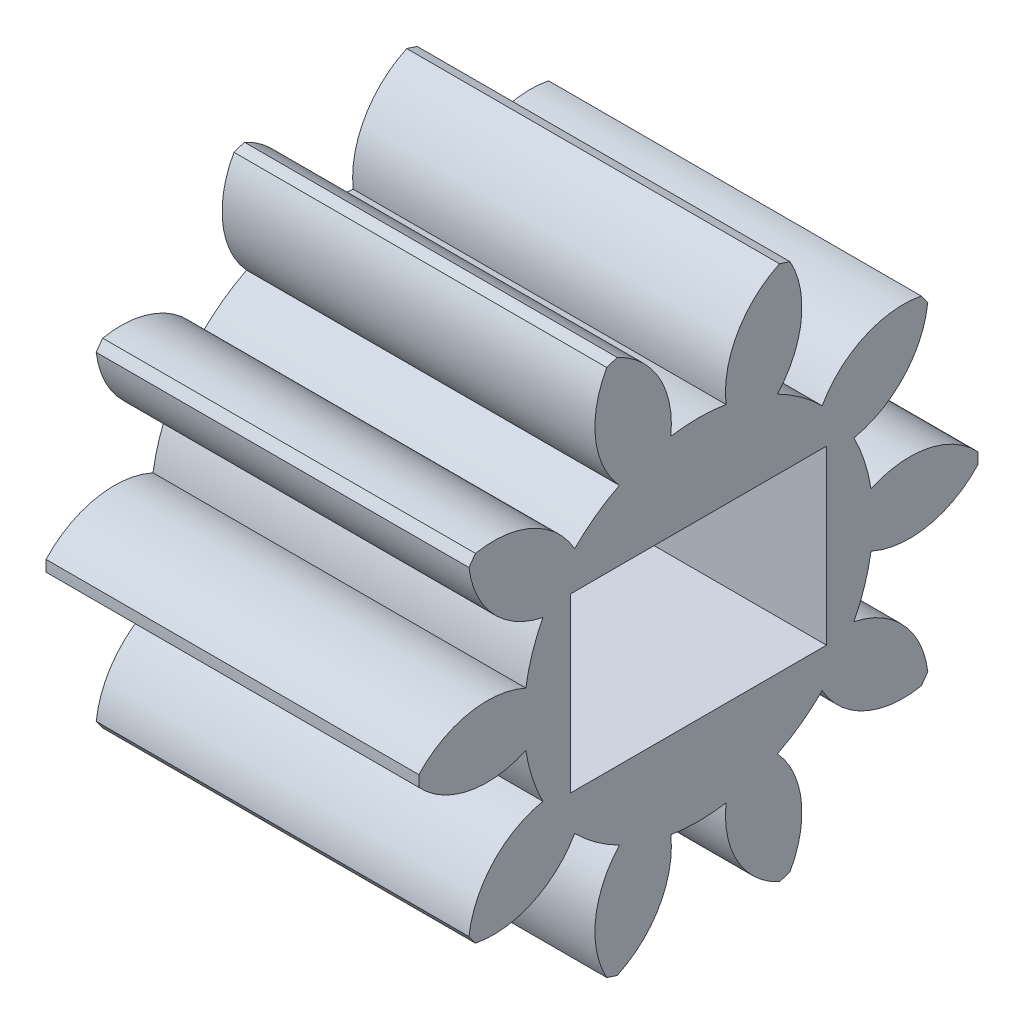
SolidWorks part; units mm, degrees
ref_plane "Plane1" through (0, 0, 0) normal (0, 0, 1) x (1, 0, 0)
ref_plane "Plane2" through (0, 0, 0) normal (0, 1, 0) x (1, 0, 0)
ref_plane "Plane3" through (0, 0, 0) normal (1, 0, 0) x (0, 0, -1)
sketch "HoldingSke" plane through (0, 0, 0) normal (0, 1, 0) x (1, 0, 0)
  line L0 (0, 0) -> (0.9848, -0.1736)
  line L1 (-15, 0) -> (100, 0) construction
  line L2 (0, 0) -> (-2.1039, 2.3779)
  line L3 (0, 0) -> (-11.863, 4.5341)
  line L4 (0, 0) -> (8.5048, 1.4996)
  line L5 (0, 0) -> (-46.8476, -17.4728)
  line L6 (0, 0) -> (-6.6317, -4.4744)
  line L7 (-2.1039, 2.3779) -> (8.6586, 51.2059)
  line L8 (-76.2, 54.61) -> (-76.1, 54.61)
  line L9 (-71.009, 38.7566) -> (-53.1078, 45.2721)
  line L10 (-76.2, 71.12) -> (104.1128, 71.12)
  line L11 (0, 0) -> (-8, 0)
  line L12 (-76.2, 101.6) -> (-76.162, 101.6)
  line L13 (24.9733, 27.94) -> (52.9518, 28.4284)
  line L14 (24.9733, 27.94) -> (24.9743, 27.94)
  line L15 (24.9733, 27.94) -> (100.4006, 29.5858)
  line L16 (-63.627, -1) -> (-12.827, -1)
  circle A0 centre (0, 0) radius 0.4
  circle A1 centre (0, 0) radius 3.749
  circle A2 centre (0, 0) radius 37.5
  circle A3 centre (0, 0) radius 0.4
  dimension "MHD" = 7.498
  dimension "Hub_dia" = 75
  dimension "Bore" = 0.8
  dimension "MBD" = 0.8
  dimension "Num_teeth" = 10
  dimension "Pitch" = 1
  dimension "Overall_len" = 50
  dimension "Show_teeth" = 10
  dimension "Thickness" = 8
  dimension "OAL" = 50.0001
  dimension "T_dim" = 0.1
  dimension "Ap" = 20
  dimension "H" = 19.05
  dimension "Pitch_radius" = 180.3128
  dimension "Width" = 8
  dimension "Backlash" = 0.038
  dimension "Addendum_fac" = 1
  dimension "Dedendum_fac" = 1.25
  dimension "Clearance_fac" = 0.25
  dimension "Dedendum_add" = 0.001
  dimension "Module" = 1
sketch "BasProSke" plane through (0, 0, 0) normal (0, 1, 0) x (1, 0, 0)
  line L0 (-10, 0) -> (60, 0) construction
  line L1 (0, 0) -> (0, 6)
  line L2 (0, 0) -> (8, 0)
  line L3 (8, 0) -> (8, 6)
  line L4 (8, 6) -> (0, 6)
  dimension "Thickness" = 8
  dimension "Diameter" = 12
revolve "Base-Revolve" add sketch "BasProSke" angle 360 about L0
sketch "TooCutSke" plane through (0, 0, 0) normal (1, 0, 0) x (0, 0, -1)
  line L1 (0, 0) -> (0, 107) construction
  line L2 (0, 0) -> (-0.8485, 4.9275) construction
  line L3 (0, 0) -> (-3.0584, 9.4126) construction
  line L4 (-0.8485, 4.9275) -> (-1.5292, 4.7063) construction
  arc A0 (0.5928, 3.7018) -> (-0.5928, 3.7018) centre (0, 0) ccw
  arc A1 (1.7758, 5.7578) -> (-1.7758, 5.7578) centre (0, 0) ccw
  circle A2 centre (0, 0) radius 5 construction
  circle A3 centre (0, 0) radius 4.6985 construction
  arc A4 (-0.5928, 3.7018) -> (-1.7758, 5.7578) centre (-2.5801, 3.9267) ccw
  arc A5 (1.7758, 5.7578) -> (0.5928, 3.7018) centre (2.5801, 3.9267) ccw
  dimension "Root_dia" = 7.498
  dimension "Overcut_dia" = 12.0508
  dimension "Pitch_dia" = 10
  dimension "Base_dia" = 9.3969
  dimension "Flank_rad" = 2
  dimension "Half_ang" = 18
  dimension "Half_CT" = 0.7157
extrude "ToothCut" cut sketch "TooCutSke" along normal through all
fillet "Breaks" [suppressed] radius 0.02
fillet "RootFillets" [suppressed] radius 0.251
pattern_circular "TeethCuts" count 10 every 36 about axis through (-10, 0, 0) along (1, 0, 0) of "ToothCut", "RootFillets", "Breaks"
sketch "HubNeaOneSke" plane through (0, 0, 0) normal (-1, 0, 0) x (0, 0, 1)
  circle A0 centre (0, 0) radius 3.749
  dimension "Diameter" = 7.498
extrude "HubNearOne" [suppressed] add sketch "HubNeaOneSke" along normal blind 42.0001
sketch "HubNeaBotSke" plane through (0, 0, 0) normal (-1, 0, 0) x (0, 0, 1)
  circle A0 centre (0, 0) radius 3.749
  dimension "Diameter" = 7.498
extrude "HubNearBoth" [suppressed] add sketch "HubNeaBotSke" along normal blind 21
ref_plane "FarPln" through (8, 0, 0) normal (1, 0, 0) x (0, 0, -1)
sketch "HubFarSke" plane through (8, 0, 0) normal (1, 0, 0) x (0, 0, -1)
  circle A0 centre (0, 0) radius 3.749
  dimension "Diameter" = 7.498
extrude "HubFar" [suppressed] add sketch "HubFarSke" along normal blind 21
sketch "BorSke" plane through (0, 0, 0) normal (1, 0, 0) x (0, 0, -1)
  circle A0 centre (0, 0) radius 0.4
  dimension "Diameter" = 0.8
extrude "Bore" cut sketch "BorSke" along normal mid plane 100.0001
sketch "KeySke" plane through (0, 0, 0) normal (1, 0, 0) x (0, 0, -1)
  line L0 (-0.05, 0) -> (-0.05, 0.5)
  line L1 (-0.05, 0.5) -> (0.05, 0.5)
  line L2 (0.05, 0.5) -> (0.05, 0)
  line L3 (0, 0) -> (0, 34) construction
  line L4 (-0.05, 0) -> (0.05, 0)
  dimension "Offset" = 0.5
  dimension "Width" = 0.1
extrude "Keyway" [suppressed] cut sketch "KeySke" along normal mid plane 100.0001
pattern_circular "Keyway2" [suppressed] count 2 every 90 about axis through (-10, 0, 0) along (1, 0, 0)
sketch "Croquis1" plane through (8, 0, 0) normal (1, 0, 0) x (0, 0, -1)
  line L1 (-2.75, -1.85) -> (2.75, -1.85)
  line L2 (-2.75, -1.85) -> (-2.75, 1.85)
  line L3 (-2.75, 1.85) -> (2.75, 1.85)
  line L4 (2.75, -1.85) -> (2.75, 1.85)
  line L5 (-2.75, -1.85) -> (2.75, 1.85) construction
  line L6 (-2.75, 1.85) -> (2.75, -1.85) construction
  point P0 (0, 0)
  dimension "D1" = 5.5
  dimension "D2" = 3.7
extrude "Cortar-Extruir1" cut sketch "Croquis1" against normal blind 6
equation "' \"Module@HoldingSke\" = 6.35"
equation "' \"Num_teeth@HoldingSke\" = 12"
equation "' \"Ap@HoldingSke\" =  20"
equation "' \"Ap@HoldingSke\" = 20"
equation "' \"Width@HoldingSke\" = 0.5 * 25.4"
equation "' \"Hub_dia@HoldingSke\"= 1 * 25.4"
equation "' \"Hub_dia@HoldingSke\" = 1 * 25.4"
equation "' \"Overall_len@HoldingSke\" = 1.0 * 25.4"
equation "' \"Bore@HoldingSke\" = 0.75 * 25.4"
equation "' \"T_dim@HoldingSke\" = 0.1 * 25.4"
equation "' \"Width@KeySke\" = 0.25 * 25.4"
equation "' \"Show_teeth@HoldingSke\" = 13"
equation "' \"Backlash@HoldingSke\" = 0.009 * 25.4"
equation "' \"Addendum_fac@HoldingSke\" = 1.0"
equation "' \"Dedendum_fac@HoldingSke\" = 1.25"
equation "' \"Dedendum_add@HoldingSke\" = 0.00005 * 25.4"
equation "' \"Clearance_fac@HoldingSke\" = 0.25"
equation "\"Pitch@HoldingSke\" = 1 / \"Module@HoldingSke\""
equation "\"Overcut_dia@TooCutSke\" = (\"Num_teeth@HoldingSke\" + 2 * \"Addendum_fac@HoldingSke\") / \"Pitch@HoldingSke\" + 0.002 * 25.4"
equation "\"Pitch_dia@TooCutSke\" = \"Num_teeth@HoldingSke\" / \"Pitch@HoldingSke\""
equation "\"Base_dia@TooCutSke\" = \"Num_teeth@HoldingSke\" / \"Pitch@HoldingSke\" * cos((\"Ap@HoldingSke\"  * 3.14159265 / 180))"
equation "\"Root_dia@TooCutSke\" = (\"Num_teeth@HoldingSke\" + 2) / \"Pitch@HoldingSke\" - 2 * (\"Addendum_fac@HoldingSke\" + \"Dedendum_fac@HoldingSke\") / \"Pitch@HoldingSke\" - \"Dedendum_add@HoldingSke\" * 2"
equation "\"Half_ang@TooCutSke\" = 180 / \"Num_teeth@HoldingSke\""
equation "\"Half_CT@TooCutSke\" = \"Num_teeth@HoldingSke\" / \"Pitch@HoldingSke\" * sin((3.14159265 / 2 / \"Num_teeth@HoldingSke\")) / 2 - 7 * \"Backlash@HoldingSke\" / 4"
equation "\"Flank_rad@TooCutSke\" = \"Num_teeth@HoldingSke\" / \"Pitch@HoldingSke\" / 5"
equation "\"Radius@RootFillets\" = \"Clearance_fac@HoldingSke\" / \"Pitch@HoldingSke\" + \"Dedendum_add@HoldingSke\""
equation "\"Break_rad@Breaks\" = 0.02 / \"Pitch@HoldingSke\""
equation "\"Thickness@HoldingSke\" = \"Width@HoldingSke\""
equation "\"OAL@HoldingSke\" = \"Thickness@HoldingSke\""
equation "\"MHD@HoldingSke\" = (\"Num_teeth@HoldingSke\" + 2) / \"Pitch@HoldingSke\" - 2 * (\"Addendum_fac@HoldingSke\" + \"Dedendum_fac@HoldingSke\")  / \"Pitch@HoldingSke\" - \"Dedendum_add@HoldingSke\" * 2"
equation "\"MBD@HoldingSke\" = (\"Num_teeth@HoldingSke\" + 2) / \"Pitch@HoldingSke\" - 2 * (\"Addendum_fac@HoldingSke\" + \"Dedendum_fac@HoldingSke\")  / \"Pitch@HoldingSke\" - \"Dedendum_add@HoldingSke\" * 2 - 0.002 * 25.4"
equation "\"MHD@HoldingSke\" = ((sgn( \"MHD@HoldingSke\" - \"Hub_dia@HoldingSke\" )-1)*( \"MHD@HoldingSke\" - \"Hub_dia@HoldingSke\" ))/-2+ \"Hub_dia@HoldingSke\""
equation "\"MBD@HoldingSke\" = ((sgn( \"MBD@HoldingSke\" - \"Bore@HoldingSke\" )-1)*( \"MBD@HoldingSke\" - \"Bore@HoldingSke\" ))/-2+ \"Bore@HoldingSke\""
equation "\"OAL@HoldingSke\" = ((sgn( \"OAL@HoldingSke\" - \"Overall_len@HoldingSke\" )+1)*( \"OAL@HoldingSke\" - \"Overall_len@HoldingSke\" ))/2 + \"Overall_len@HoldingSke\" + 0.000002 * 25.4"
equation "\"Num_teeth@TeethCuts\" = int( \"Show_teeth@HoldingSke\" ) + 1"
equation "\"Num_teeth@TeethCuts\" = ((sgn( \"Num_teeth@TeethCuts\" - \"Num_teeth@HoldingSke\" )-1)*( \"Num_teeth@TeethCuts\" - \"Num_teeth@HoldingSke\" ))/-2+ \"Num_teeth@HoldingSke\""
equation "\"Num_teeth@TeethCuts\" = ((sgn( \"Num_teeth@TeethCuts\" - 2.0)+1)*( \"Num_teeth@TeethCuts\" - 2.0))/2 +2.0"
equation "\"Angle@TeethCuts\" = 360.0 / \"Num_teeth@HoldingSke\""
equation "\"Diameter@BasProSke\" = (\"Num_teeth@HoldingSke\" + 2 * \"Addendum_fac@HoldingSke\") / \"Pitch@HoldingSke\""
equation "\"Thickness@BasProSke\"  = \"Thickness@HoldingSke\""
equation "' \"Fillet_rad@BasProSke\" =  \"Thickness@HoldingSke\" * 0.05"
equation "' \"Fillet_rad@BasProSke\" = \"Thickness@HoldingSke\" * 0.05"
equation "\"MHD@HoldingSke\" = ((sgn( \"MHD@HoldingSke\" - \"Root_dia@TooCutSke\" )-1)*( \"MHD@HoldingSke\" - \"Root_dia@TooCutSke\" ))/-2+ \"Root_dia@TooCutSke\""
equation "\"Diameter@HubNeaOneSke\" = \"MHD@HoldingSke\""
equation "\"Length@HubNearOne\" = \"OAL@HoldingSke\" - \"Thickness@BasProSke\""
equation "\"Diameter@HubNeaBotSke\" = \"MHD@HoldingSke\""
equation "\"Length@HubNearBoth\" = ( \"OAL@HoldingSke\" - \"Thickness@BasProSke\" ) / 2.0"
equation "\"Thickness@FarPln\" = \"Thickness@BasProSke\""
equation "\"Diameter@HubFarSke\" = \"MHD@HoldingSke\""
equation "\"Length@HubFar\" = ( \"OAL@HoldingSke\" - \"Thickness@BasProSke\" ) / 2.0"
equation "\"Diameter@BorSke\" = \"MBD@HoldingSke\""
equation "\"D1@Bore\" = \"OAL@HoldingSke\" * 2.0"
equation "\"D1@Keyway\" = \"OAL@HoldingSke\" * 2.0"
equation "\"Offset@KeySke\" = \"T_dim@HoldingSke\" + \"MBD@HoldingSke\" / 2.0"
